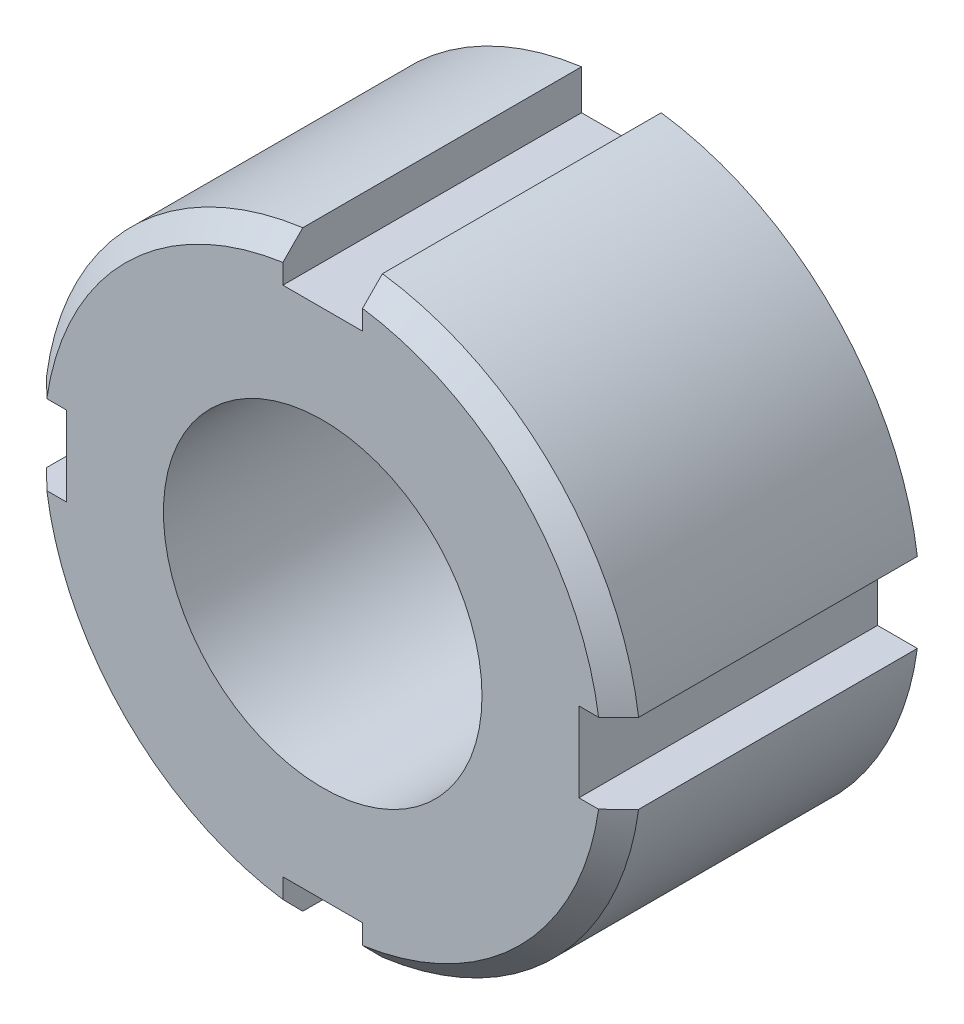
SolidWorks part; units mm, degrees
material "AISI 1020"
ref_plane "Front Plane" through (0, 0, 0) normal (0, 0, 1) x (1, 0, 0)
ref_plane "Top Plane" through (0, 0, 0) normal (0, 1, 0) x (1, 0, 0)
ref_plane "Right Plane" through (0, 0, 0) normal (1, 0, 0) x (0, 0, -1)
sketch "Sketch1" plane through (0, 0, 0) normal (0, 0, 1) x (1, 0, 0)
  circle A0 centre (0, 0) radius 15
  dimension "D1" = 30
extrude "Boss-Extrude1" add sketch "Sketch1" along normal blind 15
sketch "Sketch2" plane through (0, 0, 15) normal (0, 0, 1) x (1, 0, 0)
  line L0 (0, 16.972) -> (0, -18.0177) construction
  line L1 (-2, 14.8661) -> (-2, 12.8661)
  line L2 (-2, 12.8661) -> (2, 12.8661)
  line L3 (2, 12.8661) -> (2, 14.8661)
  line L4 (14.8661, 2) -> (12.8661, 2)
  line L5 (12.8661, 2) -> (12.8661, -2)
  line L6 (12.8661, -2) -> (14.8661, -2)
  line L7 (2, -14.8661) -> (2, -12.8661)
  line L8 (2, -12.8661) -> (-2, -12.8661)
  line L9 (-2, -12.8661) -> (-2, -14.8661)
  line L10 (-14.8661, -2) -> (-12.8661, -2)
  line L11 (-12.8661, -2) -> (-12.8661, 2)
  line L12 (-12.8661, 2) -> (-14.8661, 2)
  circle A0 centre (0, 0) radius 15 construction
  arc A1 (-2, 14.8661) -> (2, 14.8661) centre (0, 0) cw
  arc A2 (14.8661, 2) -> (14.8661, -2) centre (0, 0) cw
  arc A3 (2, -14.8661) -> (-2, -14.8661) centre (0, 0) cw
  arc A4 (-14.8661, -2) -> (-14.8661, 2) centre (0, 0) cw
  point P7 (0, 12.8661)
  point P26 (0, 0)
  dimension "D1" = 2
  dimension "D2" = 2
  dimension "D3" = 2
  dimension "D4" = 4
extrude "Cut-Extrude1" cut sketch "Sketch2" against normal through all
sketch "Sketch3" plane through (0, 0, 15) normal (0, 0, 1) x (1, 0, 0)
  circle A0 centre (0, 0) radius 8
  dimension "D1" = 16
extrude "Cut-Extrude2" cut sketch "Sketch3" against normal through all
cosmetic thread "Cosmetic Thread1" parameters "D2"=18
chamfer "Chamfer1" distance 1 angle 45 4 edges at (10.6066, -10.6066, 15) (-10.6066, -10.6066, 15) (-10.6066, 10.6066, 15) (10.6066, 10.6066, 15)
